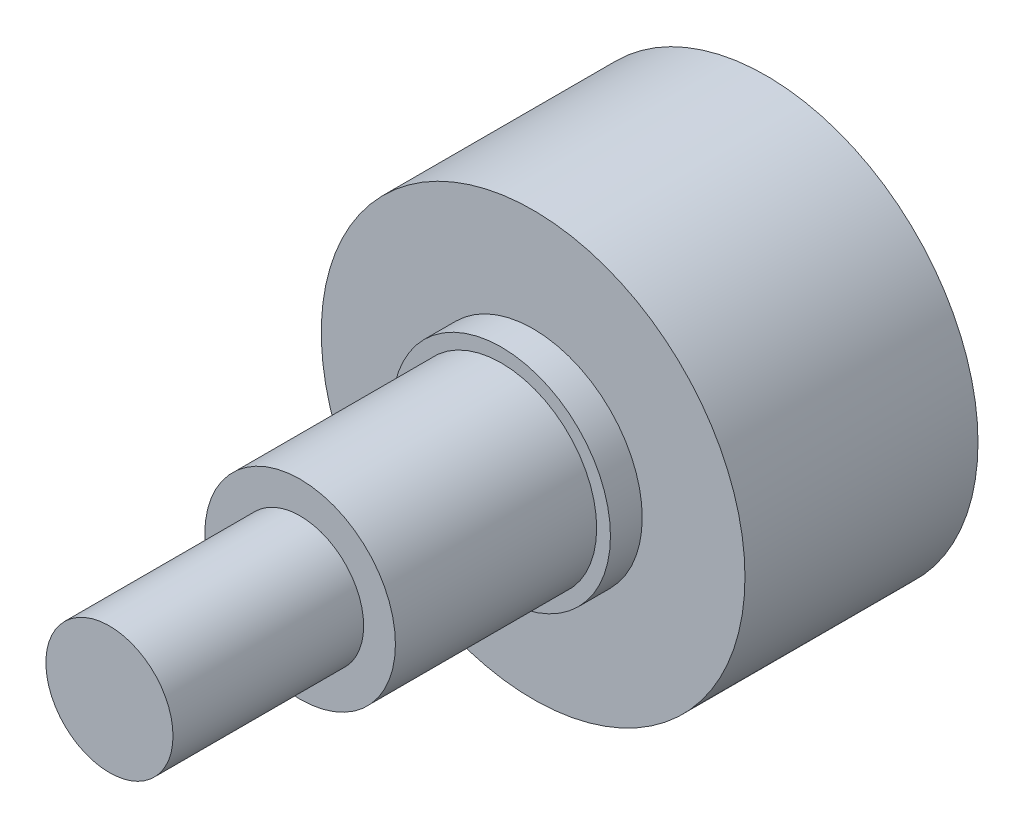
SolidWorks part; units mm, degrees
ref_plane "Front" through (0, 0, 0) normal (0, 0, 1) x (1, 0, 0)
ref_plane "Top" through (0, 0, 0) normal (0, 1, 0) x (1, 0, 0)
ref_plane "Right" through (0, 0, 0) normal (1, 0, 0) x (0, 0, -1)
sketch "Sketch1" plane through (0, 0, 0) normal (0, 0, 1) x (1, 0, 0)
  circle A0 centre (0, 0) radius 10
  dimension "D1" = 20
extrude "Boss-Extrude1" add sketch "Sketch1" along normal blind 11
sketch "Sketch2" plane through (0, 0, 11) normal (0, 0, 1) x (1, 0, 0)
  circle A0 centre (0, 0) radius 5.15
  dimension "D1" = 10.3
extrude "Boss-Extrude2" add sketch "Sketch2" along normal blind 1.5
sketch "Sketch3" plane through (0, 0, 12.5) normal (0, 0, 1) x (1, 0, 0)
  circle A0 centre (0, 0) radius 4.5
  dimension "D1" = 9
extrude "Boss-Extrude3" add sketch "Sketch3" along normal blind 9.5
sketch "Sketch4" plane through (0, 0, 22) normal (0, 0, 1) x (1, 0, 0)
  circle A0 centre (0, 0) radius 3
  dimension "D1" = 6
extrude "Boss-Extrude4" add sketch "Sketch4" along normal blind 9
